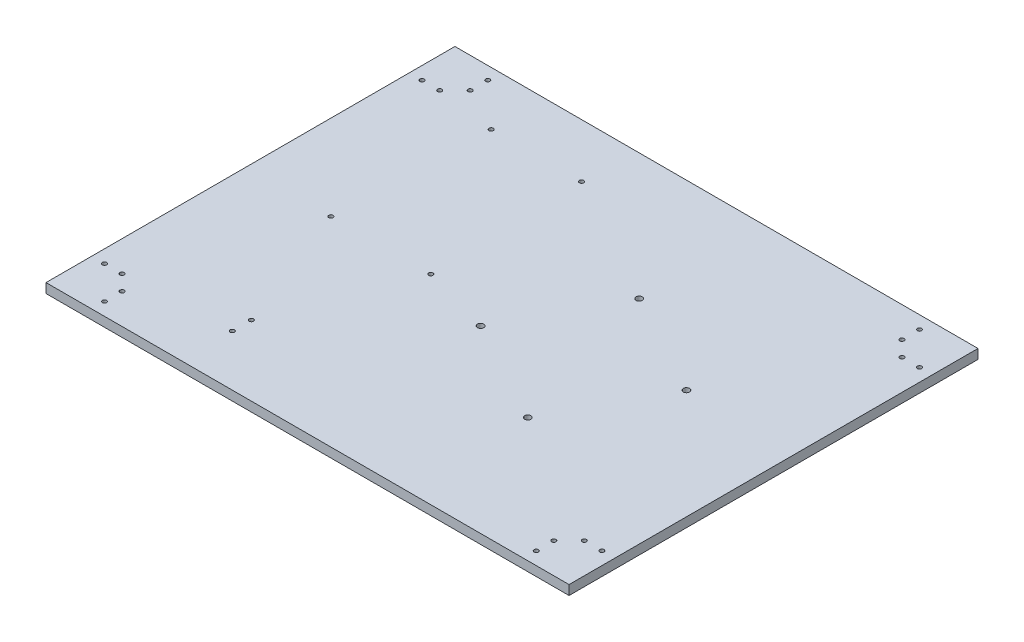
SolidWorks part; units mm, degrees
material "Multistrato di pioppo"
ref_plane "Piano frontale" through (0, 0, 0) normal (0, 0, 1) x (1, 0, 0)
ref_plane "Piano superiore" through (0, 0, 0) normal (0, 1, 0) x (1, 0, 0)
ref_plane "Piano destro" through (0, 0, 0) normal (1, 0, 0) x (0, 0, -1)
sketch "Schizzo1" plane through (0, 0, 0) normal (0, 1, 0) x (1, 0, 0)
  line L1 (-275, 215) -> (275, 215)
  line L2 (-275, 215) -> (-275, -215)
  line L3 (-275, -215) -> (275, -215)
  line L4 (275, 215) -> (275, -215)
  line L5 (-275, 215) -> (275, -215) construction
  line L6 (-275, -215) -> (275, 215) construction
  point P4 (0, 0)
  dimension "D1" = 550
  dimension "D2" = 430
extrude "Estrusione-Estrusione1" add sketch "Schizzo1" along normal blind 10
sketch "Schizzo2" plane through (0, 10, 0) normal (0, 1, 0) x (1, 0, 0)
  circle A0 centre (-227, 201.5) radius 2.25
  circle A1 centre (-227, 183) radius 2.25
  circle A2 centre (-243, 167) radius 2.25
  circle A3 centre (-261.5, 167) radius 2.25
  circle A4 centre (227, 201.5) radius 2.25
  circle A5 centre (227, 183) radius 2.25
  circle A6 centre (243, 167) radius 2.25
  circle A7 centre (261.5, 167) radius 2.25
  circle A8 centre (261.5, -167) radius 2.25
  circle A9 centre (243, -167) radius 2.25
  circle A10 centre (227, -183) radius 2.25
  circle A11 centre (227, -201.5) radius 2.25
  circle A12 centre (-227, -201.5) radius 2.25
  circle A13 centre (-227, -183) radius 2.25
  circle A14 centre (-243, -167) radius 2.25
  circle A15 centre (-261.5, -167) radius 2.25
  point P48 (0, 0)
  point P49 (0, 0)
  point P50 (-243, 167)
  point P52 (-261.5, 167)
  point P54 (0, 0)
  point P55 (-227, 183)
  point P57 (0, 0)
  point P58 (-227, 201.5)
  point P60 (0, 0)
  point P61 (227, 201.5)
  point P63 (0, 0)
  point P64 (227, 183)
  point P66 (0, 0)
  point P67 (243, 167)
  point P69 (0, 0)
  point P70 (261.5, 167)
  point P72 (0, 0)
  point P73 (243, -167)
  point P75 (0, 0)
  point P76 (0, 0)
  point P77 (261.5, -167)
  point P79 (0, 0)
  point P80 (227, -183)
  point P82 (0, 0)
  point P83 (227, -201.5)
  point P85 (0, 0)
  point P86 (-227, -201.5)
  point P88 (0, 0)
  point P89 (-227, -183)
  point P91 (0, 0)
  point P92 (-243, -167)
  point P94 (0, 0)
  point P95 (-261.5, -167)
  point P96 (0, 0)
  point P97 (-261.5, -167)
  dimension "D1" = 4.5
extrude "Taglio-Estrusione1" cut sketch "Schizzo2" against normal blind 20
sketch "Schizzo4" plane through (0, 10, 0) normal (0, 1, 0) x (1, 0, 0)
  line L4 (-7.0471, -25.9509) -> (76.3399, -1.1397) construction
  line L5 (76.3399, -1.1397) -> (51.5287, 82.2474) construction
  line L6 (76.3399, -1.1397) -> (101.1512, -84.5267) construction
  line L7 (-275, -215) -> (275, -215) construction
  line L8 (275, -215) -> (275, 215) construction
  line L9 (76.3399, -1.1397) -> (159.727, 23.6716) construction
  line L10 (76.3399, -1.1397) -> (163.3399, -1.1397) construction
  circle A1 centre (101.1512, -84.5267) radius 3.3
  circle A2 centre (159.727, 23.6716) radius 3.3
  circle A3 centre (51.5287, 82.2474) radius 3.3
  circle A4 centre (76.3399, -1.1397) radius 87 construction
  circle A5 centre (-7.0471, -25.9509) radius 3.3
  point P1 (-15.0471, -25.9509)
  dimension "D1" = 6.6
  dimension "D3" = 16.57
  dimension "D4" = 213.8603
  dimension "D5" = 198.6601
  dimension "D2" = 174
extrude "Taglio-Estrusione2" cut sketch "Schizzo4" against normal blind 10
sketch "Schizzo5" plane through (0, 0, 0) normal (0, -1, 0) x (1, 0, 0)
  line L0 (-275, -215) -> (-275, 215) construction
  line L1 (-275, 215) -> (275, 215) construction
  line L2 (-132.9216, 161.1352) -> (-132.9216, 141.1352) construction
  circle A2 centre (-132.9216, 161.1352) radius 2.25
  circle A3 centre (-132.9216, 141.1352) radius 2.25
  dimension "D4" = 4.5
  dimension "D1" = 20
  dimension "D2" = 142.0784
  dimension "D3" = 73.8648
extrude "Taglio-Estrusione3" cut sketch "Schizzo5" against normal blind 10
sketch "Schizzo6" plane through (0, 10, 0) normal (0, 1, 0) x (1, 0, 0)
  line L0 (-275, 0) -> (-257.3, 0)
  line L3 (-275, 215) -> (-275, -215) construction
  line L4 (-257.3, 0) -> (-264.8, 10)
  line L5 (-264.8, 10) -> (-229.4, 10)
  line L6 (-229.4, 10) -> (-236.9, 0)
  line L7 (-236.9, 0) -> (-219.2, 0)
  line L8 (-257.3, 0) -> (-236.9, 0) construction
  line L9 (-247.1, 0) -> (-247.1, 10) construction
  line L11 (-219.2, 0) -> (-202.3889, 0)
  line L12 (-202.3889, 0) -> (-209.8889, 10)
  line L13 (-209.8889, 10) -> (-174.4889, 10)
  line L14 (-174.4889, 10) -> (-181.9889, 0)
  line L15 (-181.9889, 0) -> (-165.1778, 0)
  line L16 (-202.3889, 0) -> (-181.9889, 0) construction
  line L17 (-192.1889, 0) -> (-192.1889, 10) construction
  line L18 (-165.1778, 0) -> (-147.4778, 0)
  line L19 (-147.4778, 0) -> (-154.9778, 10)
  line L20 (-154.9778, 10) -> (-119.5778, 10)
  line L21 (-119.5778, 10) -> (-127.0778, 0)
  line L22 (-127.0778, 0) -> (-110.2667, 0)
  line L23 (-147.4778, 0) -> (-127.0778, 0) construction
  line L24 (-137.2778, 0) -> (-137.2778, 10) construction
  line L25 (-110.2667, 0) -> (-92.5667, 0)
  line L26 (-92.5667, 0) -> (-100.0667, 10)
  line L27 (-100.0667, 10) -> (-64.6667, 10)
  line L28 (-64.6667, 10) -> (-72.1667, 0)
  line L29 (-72.1667, 0) -> (-55.3556, 0)
  line L30 (-92.5667, 0) -> (-72.1667, 0) construction
  line L31 (-82.3667, 0) -> (-82.3667, 10) construction
  line L32 (-55.3556, 0) -> (-37.6556, 0)
  line L33 (-37.6556, 0) -> (-45.1556, 10)
  line L34 (-45.1556, 10) -> (-9.7556, 10)
  line L35 (-9.7556, 10) -> (-17.2556, 0)
  line L36 (-17.2556, 0) -> (-0.4444, 0)
  line L37 (-37.6556, 0) -> (-17.2556, 0) construction
  line L38 (-27.4556, 0) -> (-27.4556, 10) construction
  line L39 (-0.4444, 0) -> (17.2556, 0)
  line L40 (17.2556, 0) -> (9.7556, 10)
  line L41 (9.7556, 10) -> (45.1556, 10)
  line L42 (45.1556, 10) -> (37.6556, 0)
  line L43 (37.6556, 0) -> (54.4667, 0)
  line L44 (17.2556, 0) -> (37.6556, 0) construction
  line L45 (27.4556, 0) -> (27.4556, 10) construction
  line L46 (54.4667, 0) -> (72.1667, 0)
  line L47 (72.1667, 0) -> (64.6667, 10)
  line L48 (64.6667, 10) -> (100.0667, 10)
  line L49 (100.0667, 10) -> (92.5667, 0)
  line L50 (92.5667, 0) -> (109.3778, 0)
  line L51 (72.1667, 0) -> (92.5667, 0) construction
  line L52 (82.3667, 0) -> (82.3667, 10) construction
  line L53 (109.3778, 0) -> (127.0778, 0)
  line L54 (127.0778, 0) -> (119.5778, 10)
  line L55 (119.5778, 10) -> (154.9778, 10)
  line L56 (154.9778, 10) -> (147.4778, 0)
  line L57 (147.4778, 0) -> (164.2889, 0)
  line L58 (127.0778, 0) -> (147.4778, 0) construction
  line L59 (137.2778, 0) -> (137.2778, 10) construction
  line L60 (164.2889, 0) -> (181.9889, 0)
  line L61 (181.9889, 0) -> (174.4889, 10)
  line L62 (174.4889, 10) -> (209.8889, 10)
  line L63 (209.8889, 10) -> (202.3889, 0)
  line L64 (202.3889, 0) -> (219.2, 0)
  line L65 (181.9889, 0) -> (202.3889, 0) construction
  line L66 (192.1889, 0) -> (192.1889, 10) construction
  line L67 (219.2, 0) -> (236.9, 0)
  line L68 (236.9, 0) -> (229.4, 10)
  line L69 (229.4, 10) -> (264.8, 10)
  line L70 (264.8, 10) -> (257.3, 0)
  line L71 (257.3, 0) -> (275, 0)
  line L72 (236.9, 0) -> (257.3, 0) construction
  line L73 (247.1, 0) -> (247.1, 10) construction
  line L74 (275, -215) -> (275, 215) construction
  dimension "D1" = 55.8
  dimension "D2" = 10
  dimension "D3" = 35.4
  dimension "D4" = 20.4
  dimension "D5" = 10
sketch "Schizzo7" plane through (0, 10, 0) normal (0, 1, 0) x (1, 0, 0)
  line L0 (-180.3797, 158.5) -> (-85.3797, 158.5) construction
  line L1 (275, 215) -> (-275, 215) construction
  line L2 (-275, 215) -> (-275, -215) construction
  line L3 (-185.3797, -5) -> (-80.3797, -5) construction
  circle A0 centre (-180.3797, 158.5) radius 2.25
  circle A1 centre (-85.3797, 158.5) radius 2.25
  circle A2 centre (-80.3797, -5) radius 2.25
  circle A3 centre (-185.3797, -5) radius 2.25
  dimension "D1" = 4.5
  dimension "D6" = 163.5
  dimension "D2" = 95
  dimension "D3" = 56.5
  dimension "D4" = 94.6203
  dimension "D5" = 105
  dimension "D7" = 89.6203
extrude "Taglio-Estrusione4" cut sketch "Schizzo7" against normal blind 10
